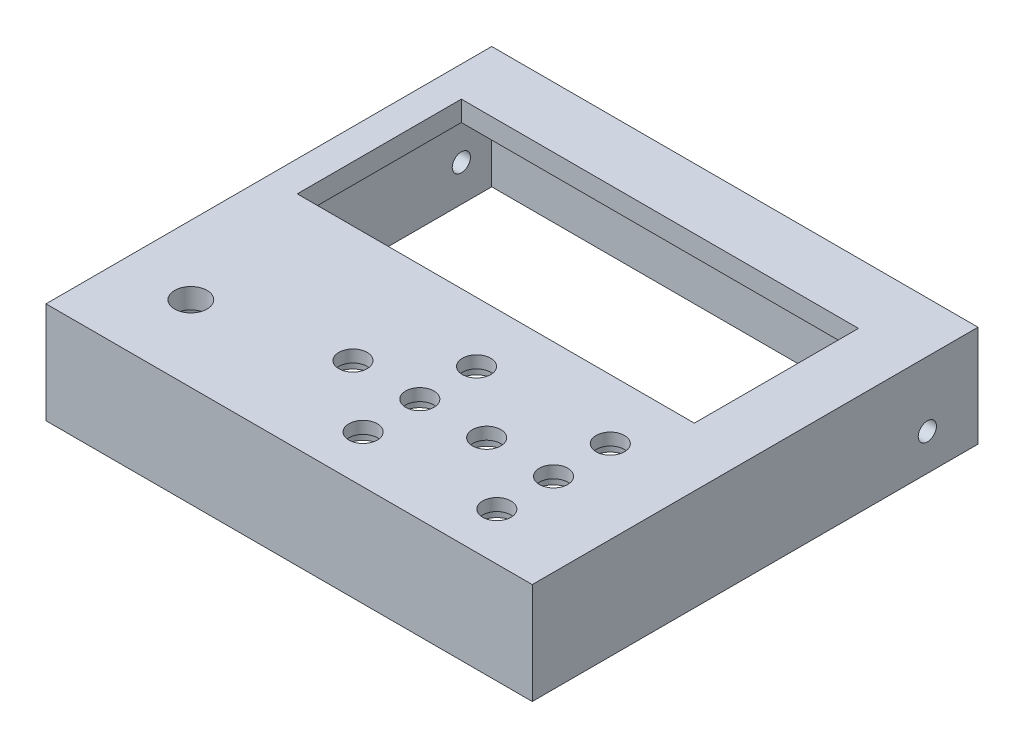
SolidWorks part; units mm, degrees
material "Printed PLA"
ref_plane "Front Plane" through (0, 0, 0) normal (0, 0, 1) x (1, 0, 0)
ref_plane "Top Plane" through (0, 0, 0) normal (0, 1, 0) x (1, 0, 0)
ref_plane "Right Plane" through (0, 0, 0) normal (1, 0, 0) x (0, 0, -1)
sketch "Sketch1" plane through (0, 0, 0) normal (0, 1, 0) x (1, 0, 0)
  line L0 (-49, 20.25) -> (49, -20.25) construction
  line L1 (-49, 20.25) -> (49, 20.25)
  line L2 (-49, 20.25) -> (-49, -20.25)
  line L3 (-49, -20.25) -> (49, -20.25)
  line L4 (49, 20.25) -> (49, -20.25)
  line L5 (-56.5, 35.25) -> (63.5, 35.25)
  line L6 (-56.5, 35.25) -> (-56.5, -74.75)
  line L7 (-56.5, -74.75) -> (63.5, -74.75)
  line L8 (63.5, 35.25) -> (63.5, -74.75)
  dimension "D1" = 98
  dimension "D2" = 40.5
  dimension "D3" = 15
  dimension "D4" = 7.5
  dimension "D5" = 110
  dimension "D6" = 120
extrude "Boss-Extrude1" add sketch "Sketch1" along normal blind 5
sketch "Sketch2" plane through (0, 0, 0) normal (0, -1, 0) x (1, 0, 0)
  line L0 (-46.5, 27.5) -> (-46.5, -27.5) construction
  line L1 (-46.5, -27.5) -> (46.5, -27.5) construction
  line L2 (46.5, -27.5) -> (46.5, 27.5) construction
  line L3 (46.5, 27.5) -> (-46.5, 27.5) construction
  line L4 (-46.5, 27.5) -> (46.5, -27.5) construction
  line L5 (-46.5, 66.5) -> (-46.5, 33.5) construction
  line L6 (-46.5, 33.5) -> (50.5, 33.5) construction
  line L7 (50.5, 33.5) -> (50.5, 66.5) construction
  line L8 (50.5, 66.5) -> (-46.5, 66.5) construction
  line L9 (-46.5, 33.5) -> (-46.5, 27.5) construction
  circle A0 centre (-46.5, 27.5) radius 1.25
  circle A1 centre (46.5, 27.5) radius 1.25
  circle A2 centre (46.5, -27.5) radius 1.25
  circle A3 centre (-46.5, -27.5) radius 1.25
  circle A4 centre (-46.5, 33.5) radius 1.25
  circle A5 centre (50.5, 33.5) radius 1.25
  circle A6 centre (50.5, 66.5) radius 1.25
  circle A7 centre (-46.5, 66.5) radius 1.25
  dimension "D1" = 2.5
  dimension "D2" = 55
  dimension "D3" = 93
  dimension "D4" = 33
  dimension "D5" = 97
  dimension "D6" = 6
extrude "Cut-Extrude1" cut sketch "Sketch2" against normal blind 4
sketch "Sketch3" plane through (0, 5, 0) normal (0, 1, 0) x (1, 0, 0)
  line L0 (-6.5, -49) -> (26.5, -49) construction
  line L1 (10, -35) -> (10, -63) construction
  line L2 (26.5, -49) -> (43, -49) construction
  line L3 (43, -35) -> (43, -63) construction
  circle A0 centre (43, -35) radius 3.5
  circle A1 centre (43, -49) radius 3.5
  circle A2 centre (43, -63) radius 3.5
  circle A3 centre (26.5, -49) radius 3.5
  circle A4 centre (10, -49) radius 3.5
  circle A5 centre (10, -35) radius 3.5
  circle A6 centre (10, -63) radius 3.5
  circle A7 centre (-6.5, -49) radius 3.5
  circle A9 centre (50.5, -33.5) radius 1.25 construction
  circle A10 centre (50.5, -33.5) radius 1.25 construction
  dimension "D1" = 7
  dimension "D5" = 16.5
  dimension "D7" = 7.5
  dimension "D6" = 1.5
  dimension "D2" = 28
  dimension "D3" = 28
  dimension "D4" = 16.5
extrude "Cut-Extrude2" cut sketch "Sketch3" against normal through all
sketch "Sketch4" plane through (0, 5, 0) normal (0, 1, 0) x (1, 0, 0)
  circle A0 centre (-39.5, -56) radius 4
  circle A1 centre (-46.5, -66.5) radius 1.25 construction
  circle A2 centre (-46.5, -66.5) radius 1.25 construction
  dimension "D1" = 7
  dimension "D2" = 10.5
  dimension "D3" = 8
extrude "Cut-Extrude3" cut sketch "Sketch4" against normal through all
sketch "Sketch5" plane through (0, 0, 0) normal (0, -1, 0) x (1, 0, 0)
  circle A0 centre (43, 63) radius 4.5
  circle A1 centre (43, 49) radius 4.5
  circle A2 centre (43, 35) radius 4.5
  circle A3 centre (26.5, 49) radius 4.5
  circle A4 centre (10, 49) radius 4.5
  circle A5 centre (10, 35) radius 4.5
  circle A6 centre (-6.5, 49) radius 4.5
  circle A7 centre (10, 63) radius 4.5
  dimension "D1" = 9
extrude "Cut-Extrude4" cut sketch "Sketch5" against normal blind 2
sketch "Sketch6" plane through (0, 0, 0) normal (0, -1, 0) x (1, 0, 0)
  line L1 (-56.5, 74.75) -> (63.5, 74.75)
  line L2 (-56.5, 74.75) -> (-56.5, -35.25)
  line L3 (-56.5, -35.25) -> (63.5, -35.25)
  line L4 (63.5, 74.75) -> (63.5, -35.25)
  line L5 (58.5, -30.25) -> (-51.5, -30.25)
  line L6 (58.5, -30.25) -> (58.5, 70.75)
  line L7 (58.5, 70.75) -> (-51.5, 70.75)
  line L8 (-51.5, -30.25) -> (-51.5, 70.75)
  dimension "D1" = 4
  dimension "D2" = 5
  dimension "D3" = 5
  dimension "D4" = 5
extrude "Boss-Extrude3" add sketch "Sketch6" along normal blind 20
sketch "Sketch7" plane through (63.5, 0, 0) normal (1, 0, 0) x (0, 0, -1)
  line L0 (22.75, -11) -> (35.25, 5) construction
  line L1 (22.75, -11) -> (35.25, -20) construction
  line L2 (35.25, 5) -> (35.25, -20) construction
  line L3 (35.25, -20) -> (-74.75, -20) construction
  circle A0 centre (22.75, -11) radius 2.25
  dimension "D1" = 4.5
  dimension "D3" = 9
  dimension "D2" = 12.5
extrude "Cut-Extrude5" cut sketch "Sketch7" against normal through all
sketch "Sketch8" plane through (0, 0, 0) normal (0, -1, 0) x (1, 0, 0)
  line L0 (-51.5, 30.5) -> (-41.5, 30.5)
  line L1 (-51.5, 70.75) -> (-51.5, -30.25) construction
  line L2 (-41.5, 30.5) -> (-41.5, 27.5)
  line L3 (-51.5, 27.5) -> (-51.5, 30.5)
  line L4 (-46.5, 33.5) -> (-46.5, 30.5) construction
  line L5 (-46.5, 30.5) -> (-46.5, 27.5) construction
  line L7 (0, 20.25) -> (0, 10.6798) construction
  line L8 (-49, 20.25) -> (49, 20.25) construction
  line L9 (-51.5, -22.5) -> (-46.5, -22.5)
  line L10 (-41.5, -27.5) -> (-41.5, -30.25)
  line L11 (-51.5, -30.25) -> (58.5, -30.25) construction
  line L12 (-41.5, -30.25) -> (-51.5, -30.25)
  line L13 (-51.5, -30.25) -> (-51.5, -22.5)
  line L14 (46.5, 30.5) -> (46.5, 27.5) construction
  line L15 (46.5, 33.5) -> (46.5, 30.5) construction
  line L16 (58.5, -30.25) -> (58.5, -22.5)
  line L17 (41.5, -30.25) -> (58.5, -30.25)
  line L18 (41.5, -27.5) -> (41.5, -30.25)
  line L19 (58.5, -22.5) -> (46.5, -22.5)
  line L20 (51.5, 27.5) -> (51.5, 30.5)
  line L21 (41.5, 30.5) -> (41.5, 27.5)
  line L22 (51.5, 30.5) -> (41.5, 30.5)
  line L23 (58.5, -30.25) -> (58.5, 70.75) construction
  arc A0 (-41.5, 27.5) -> (-51.5, 27.5) centre (-46.5, 27.5) cw
  circle A1 centre (-46.5, 27.5) radius 1.25 construction
  circle A2 centre (-46.5, 27.5) radius 1.25
  arc A3 (-46.5, -22.5) -> (-41.5, -27.5) centre (-46.5, -27.5) cw
  circle A4 centre (-46.5, -27.5) radius 1.25 construction
  circle A5 centre (-46.5, -27.5) radius 1.25
  circle A6 centre (46.5, -27.5) radius 1.25
  arc A7 (46.5, -22.5) -> (41.5, -27.5) centre (46.5, -27.5) ccw
  circle A8 centre (46.5, 27.5) radius 1.25
  arc A9 (41.5, 27.5) -> (51.5, 27.5) centre (46.5, 27.5) ccw
extrude "Boss-Extrude4" [suppressed] add sketch "Sketch8" along normal blind 4
sketch "Sketch9" plane through (0, 0, 0) normal (0, -1, 0) x (1, 0, 0)
  line L0 (-51.5, 30.625) -> (-46.5, 30.625)
  line L1 (-51.5, 70.75) -> (-51.5, -30.25) construction
  line L2 (-46.5, 24.375) -> (-51.5, 24.375)
  line L3 (-51.5, 24.375) -> (-51.5, 30.625)
  line L4 (46.5, 27.5) -> (58.5, 27.5) construction
  line L5 (58.5, -30.25) -> (58.5, 70.75) construction
  line L6 (46.5, 30.625) -> (58.5, 30.625)
  line L7 (46.5, 24.375) -> (58.5, 24.375)
  line L8 (-51.5, -24.375) -> (-46.5, -24.375)
  line L9 (-51.5, 70.75) -> (-51.5, -30.25) construction
  line L10 (-43.375, -27.5) -> (-43.375, -30.25)
  line L11 (-51.5, -30.25) -> (58.5, -30.25) construction
  line L12 (-43.375, -30.25) -> (-51.5, -30.25)
  line L13 (-51.5, -30.25) -> (-51.5, -24.375)
  line L14 (43.375, -30.25) -> (43.375, -27.5)
  line L15 (46.5, -24.375) -> (58.5, -24.375)
  line L16 (58.5, -24.375) -> (58.5, -30.25)
  line L17 (58.5, -30.25) -> (43.375, -30.25)
  circle A0 centre (-46.5, 27.5) radius 1.25
  circle A1 centre (-46.5, 27.5) radius 1.25 construction
  circle A2 centre (46.5, 27.5) radius 1.25
  circle A3 centre (46.5, -27.5) radius 1.25
  circle A4 centre (-46.5, -27.5) radius 1.25
  arc A5 (-46.5, 30.625) -> (-46.5, 24.375) centre (-46.5, 27.5) cw
  arc A6 (46.5, 30.625) -> (46.5, 24.375) centre (46.5, 27.5) ccw
  arc A7 (58.5, 24.375) -> (58.5, 30.625) centre (58.5, 27.5) ccw
  arc A8 (-46.5, -24.375) -> (-43.375, -27.5) centre (-46.5, -27.5) cw
  arc A9 (43.375, -27.5) -> (46.5, -24.375) centre (46.5, -27.5) cw
  point P20 (52.5, 27.5)
  dimension "D1" = 1.875
extrude "Boss-Extrude5" add sketch "Sketch9" along normal blind 4
sketch "Sketch10" plane through (0, 0, 0) normal (0, -1, 0) x (1, 0, 0)
  line L0 (-46.5, 33.5) -> (-51.5, 33.5) construction
  line L1 (-51.5, 70.75) -> (-51.5, 30.625) construction
  line L2 (-46.5, 30.625) -> (-51.5, 30.625)
  line L3 (-46.5, 36.375) -> (-51.5, 36.375)
  line L4 (50.5, 33.5) -> (58.5, 33.5) construction
  line L5 (58.5, 30.625) -> (58.5, 70.75) construction
  line L6 (50.5, 36.375) -> (58.5, 36.375)
  line L7 (50.5, 30.625) -> (58.5, 30.625)
  line L8 (58.5, 30.625) -> (46.5, 30.625) construction
  line L9 (-51.5, 63.625) -> (-46.5, 63.625)
  line L10 (-43.625, 66.5) -> (-43.625, 70.75)
  line L11 (58.5, 70.75) -> (-51.5, 70.75) construction
  line L12 (-43.625, 70.75) -> (-51.5, 70.75)
  line L13 (-51.5, 70.75) -> (-51.5, 63.625)
  line L14 (47.625, 70.75) -> (47.625, 66.5)
  line L15 (58.5, 70.75) -> (-51.5, 70.75) construction
  line L16 (50.5, 63.625) -> (58.5, 63.625)
  line L17 (58.5, -30.25) -> (58.5, 70.75) construction
  line L18 (58.5, 63.625) -> (58.5, 70.75)
  line L19 (58.5, 70.75) -> (47.625, 70.75)
  circle A0 centre (-46.5, 33.5) radius 1.25
  circle A1 centre (-46.5, 66.5) radius 1.25
  circle A2 centre (50.5, 66.5) radius 1.25
  circle A3 centre (50.5, 33.5) radius 1.25
  circle A4 centre (-46.5, 33.5) radius 1.25 construction
  arc A5 (-46.5, 30.625) -> (-46.5, 36.375) centre (-46.5, 33.5) ccw
  arc A6 (-51.5, 36.375) -> (-51.5, 30.625) centre (-51.5, 33.5) ccw
  arc A7 (50.5, 36.375) -> (50.5, 30.625) centre (50.5, 33.5) ccw
  arc A8 (58.5, 30.625) -> (58.5, 36.375) centre (58.5, 33.5) ccw
  arc A9 (-46.5, 63.625) -> (-43.625, 66.5) centre (-46.5, 66.5) ccw
  arc A10 (47.625, 66.5) -> (50.5, 63.625) centre (50.5, 66.5) ccw
  point P14 (-49, 33.5)
  point P22 (54.5, 33.5)
extrude "Boss-Extrude6" add sketch "Sketch10" along normal blind 11
sketch "Sketch11" plane through (0, 0, 0) normal (0, -1, 0) x (1, 0, 0)
  line L0 (-43.625, 33.5) -> (-43.375, 27.5)
  line L1 (-43.375, 27.5) -> (-46.5, 30.625)
  line L2 (-46.5, 30.625) -> (-43.625, 33.5)
  line L4 (47.625, 33.5) -> (50.5, 30.625)
  line L5 (50.5, 30.625) -> (45.4632, 30.448)
  arc A0 (-46.5, 30.625) -> (-46.5, 36.375) centre (-46.5, 33.5) ccw construction
  arc A1 (-46.5, 24.375) -> (-46.5, 30.625) centre (-46.5, 27.5) ccw construction
  arc A2 (46.5, 30.625) -> (46.5, 24.375) centre (46.5, 27.5) ccw construction
  arc A3 (50.5, 36.375) -> (50.5, 30.625) centre (50.5, 33.5) ccw construction
  arc A4 (45.4632, 30.448) -> (47.625, 33.5) centre (44.3897, 33.5) ccw
extrude "Boss-Extrude7" add sketch "Sketch11" along normal up to surface (4 mm away) up to face at (-48.2187, -4, 27.5)
